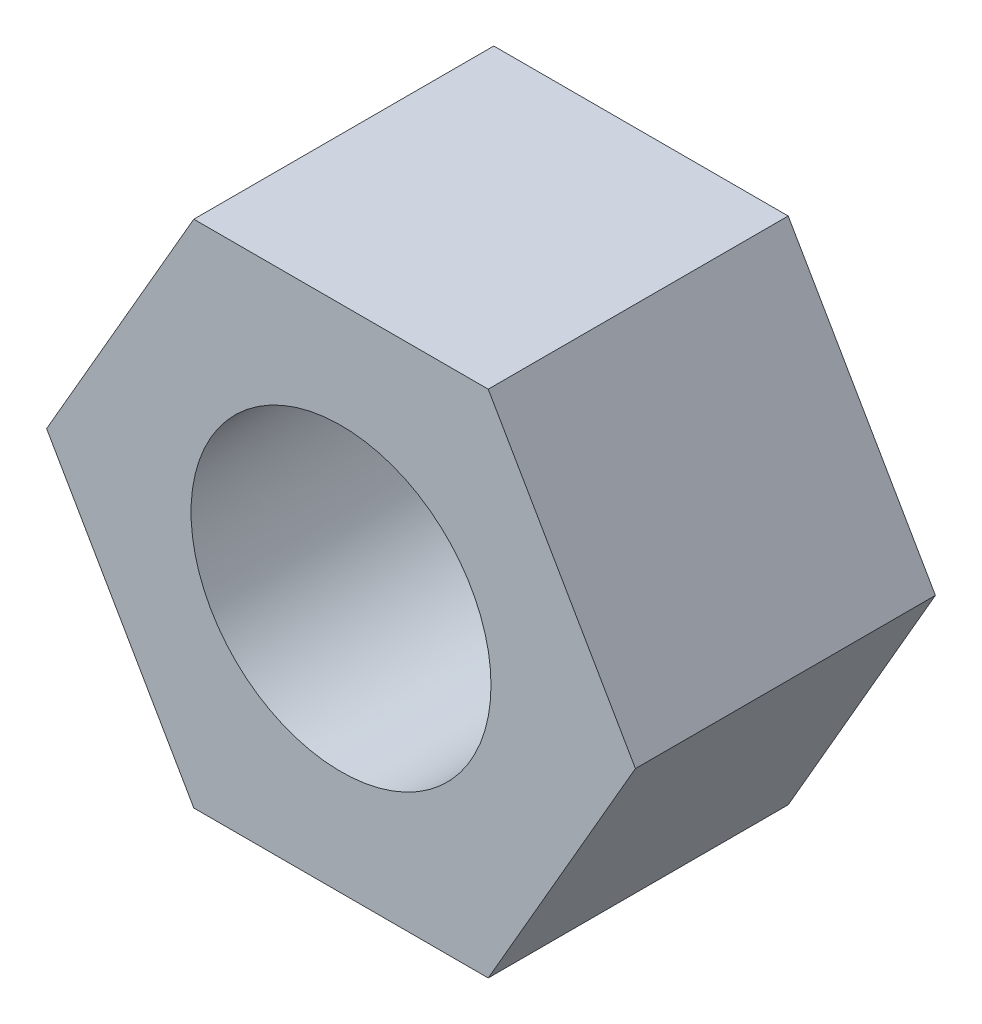
SolidWorks part; units mm, degrees
material "Chrome Stainless Steel"
ref_plane "Front Plane" through (0, 0, 0) normal (0, 0, 1) x (1, 0, 0)
ref_plane "Top Plane" through (0, 0, 0) normal (0, 1, 0) x (1, 0, 0)
ref_plane "Right Plane" through (0, 0, 0) normal (1, 0, 0) x (0, 0, -1)
sketch "Sketch1" plane through (0, 0, 0) normal (0, 0, 1) x (1, 0, 0)
  line L1 (4.9075, 0) -> (2.4537, 4.25)
  line L2 (2.4537, 4.25) -> (-2.4537, 4.25)
  line L3 (-2.4537, 4.25) -> (-4.9075, 0)
  line L4 (-4.9075, 0) -> (-2.4537, -4.25)
  line L5 (-2.4537, -4.25) -> (2.4537, -4.25)
  line L6 (2.4537, -4.25) -> (4.9075, 0)
  circle A0 centre (0, 0) radius 4.25 construction
  circle A1 centre (0, 0) radius 2.5
  circle A2 centre (0, 0) radius 4.25 construction
  dimension "D1" = 8.5
  dimension "D2" = 5
extrude "Boss-Extrude3" add sketch "Sketch1" against normal blind 5 contours A0 A1
